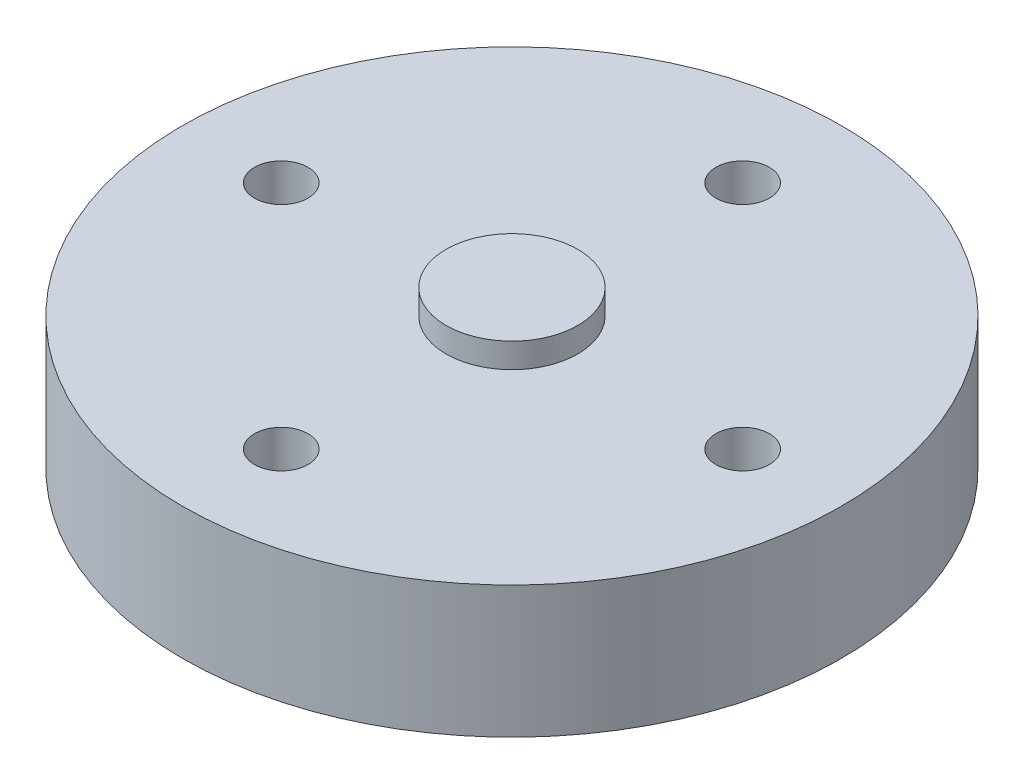
SolidWorks part; units mm, degrees
ref_plane "Alzado" through (0, 0, 0) normal (0, 0, 1) x (1, 0, 0)
ref_plane "Planta" through (0, 0, 0) normal (0, 1, 0) x (1, 0, 0)
ref_plane "Vista lateral" through (0, 0, 0) normal (1, 0, 0) x (0, 0, -1)
sketch "Croquis3" plane through (0, 0, 0) normal (0, 1, 0) x (1, 0, 0)
  circle A0 centre (0, 0) radius 20
  dimension "D1" = 40
extrude "Saliente-Extruir1" add sketch "Croquis3" along normal blind 8 contours A0
sketch "Croquis4" plane through (0, 0, 0) normal (0, 1, 0) x (1, 0, 0)
  circle A0 centre (0, 0) radius 4
  dimension "D1" = 8
extrude "Saliente-Extruir3" add sketch "Croquis4" along normal blind 1.5 from surface at 8 contours A0 starting at face at (0, 8, 20)
sketch "Croquis7" plane through (0, 8, 0) normal (0, 1, 0) x (1, 0, 0)
  circle A0 centre (-14, 0) radius 1.625
  circle A1 centre (14, 0) radius 1.625
  circle A2 centre (0, 14) radius 1.625
  circle A3 centre (0, -14) radius 1.625
  dimension "D1" = 3.25
  dimension "D2" = 3.25
  dimension "D3" = 3.25
  dimension "D4" = 3.25
  dimension "D5" = 14
  dimension "D6" = 14
  dimension "D7" = 0
  dimension "D8" = 0
  dimension "D9" = 14
  dimension "D10" = 0
  dimension "D11" = 14
  dimension "D12" = 0
extrude "Cortar-Extruir2" cut sketch "Croquis7" against normal through all from surface at 0 contours A1 | A2 | A3 | A0 starting at face at (0, 8, 4)
